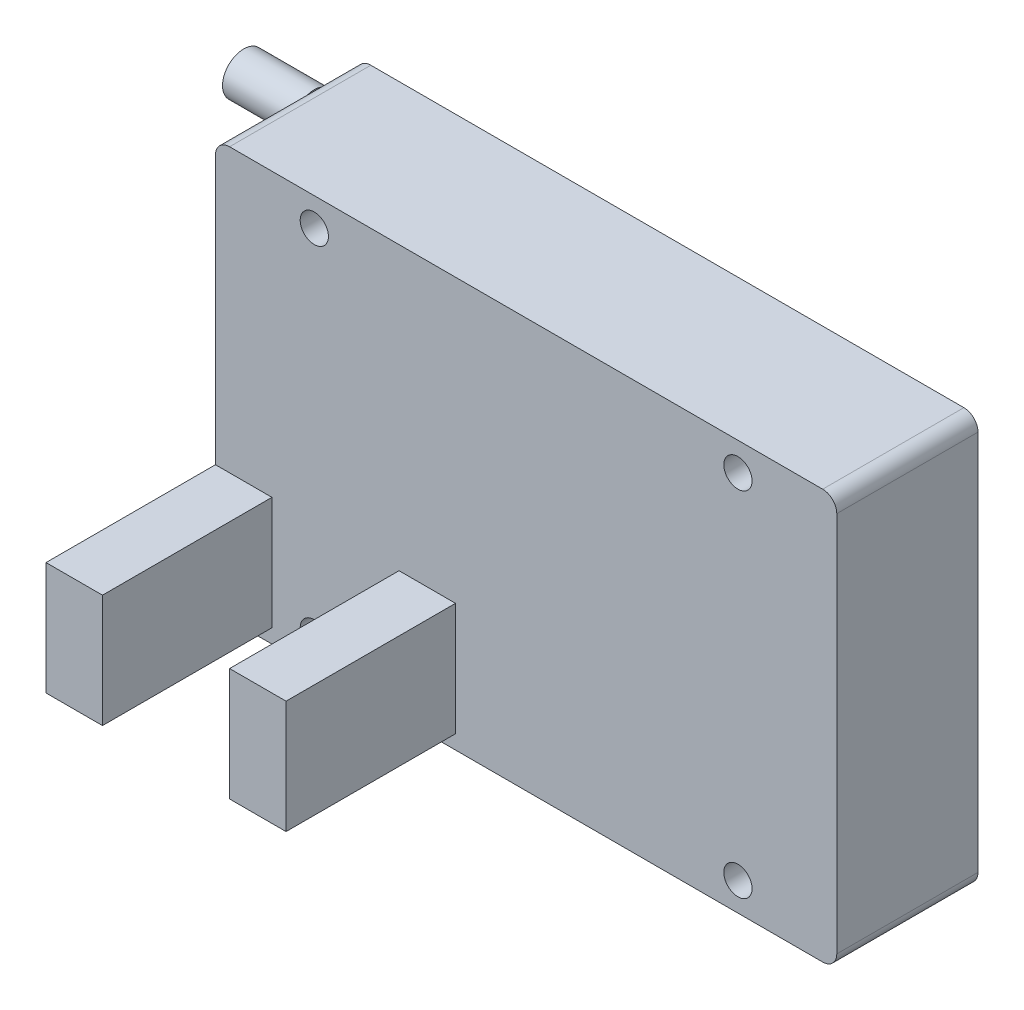
SolidWorks part; units mm, degrees
ref_plane "Front Plane" through (0, 0, 0) normal (1, 0, 0) x (0, 1, 0)
ref_plane "Top Plane" through (0, 0, 0) normal (0, 0, 1) x (0, 1, 0)
ref_plane "Right Plane" through (0, 0, 0) normal (0, 1, 0) x (-1, 0, 0)
sketch "Sketch1" plane through (0, 0, 0) normal (0, 0, 1) x (0, 1, 0)
  line L1 (-13.5, 22) -> (13.5, 22)
  line L2 (-14.5, 21) -> (-14.5, -21)
  line L3 (-13.5, -22) -> (13.5, -22)
  line L4 (14.5, 21) -> (14.5, -21)
  line L5 (-14.5, 22) -> (14.5, -22) construction
  line L6 (-14.5, -22) -> (14.5, 22) construction
  arc A0 (-14.5, -21) -> (-13.5, -22) centre (-13.5, -21) ccw
  arc A1 (13.5, -22) -> (14.5, -21) centre (13.5, -21) ccw
  arc A2 (13.5, 22) -> (14.5, 21) centre (13.5, 21) cw
  arc A3 (-13.5, 22) -> (-14.5, 21) centre (-13.5, 21) ccw
  point P0 (0, 0)
  dimension "D3" = 1
  dimension "D1" = 29
  dimension "D2" = 44
extrude "Boss-Extrude1" add sketch "Sketch1" along normal blind 10
sketch "Sketch2" plane through (-22, 0, 0) normal (-1, 0, 0) x (0, -1, 0)
  line L0 (-13.5, 3) -> (13.5, 3) construction
  line L1 (-13.5, 10) -> (-13.5, 0) construction
  line L2 (13.5, 10) -> (13.5, 0) construction
  line L3 (-14.5, 10) -> (-14.5, 0) construction
  line L4 (14.5, 10) -> (14.5, 0) construction
  line L5 (-13.5, 0) -> (13.5, 0) construction
  circle A0 centre (-12.5, 3) radius 1.5
  circle A1 centre (0.5, 3) radius 1.5
  circle A2 centre (6.5, 3) radius 1.5
  circle A3 centre (11.5, 3) radius 1.5
  dimension "D1" = 3
  dimension "D2" = 2
  dimension "D3" = 3
  dimension "D4" = 5
  dimension "D5" = 6
  dimension "D6" = 3
extrude "Boss-Extrude2" add sketch "Sketch2" along normal blind 5
sketch "Sketch3" plane through (0, 0, 10) normal (0, 0, 1) x (1, 0, 0)
  line L0 (-22, 13.5) -> (-22, -13.5) construction
  line L1 (-22, -5.5) -> (-18, -5.5)
  line L2 (-22, -5.5) -> (-22, -13.5)
  line L3 (-22, -13.5) -> (-18, -13.5)
  line L4 (-5, -5.5) -> (-5, -13.5)
  line L6 (-18, -5.5) -> (-18, -13.5)
  line L7 (-9, -5.5) -> (-9, -13.5)
  line L8 (-9, -5.5) -> (-5, -5.5)
  line L9 (-9, -13.5) -> (-5, -13.5)
  point P11 (-5, -5.5)
  line M10 (-22, 13.5) -> (-22, -13.5)
  dimension "D1" = 8
  dimension "D2" = 17
  dimension "D3" = 4
  dimension "D4" = 4
extrude "Boss-Extrude3" add sketch "Sketch3" along normal blind 12 contours L7 L9 L4 L8 | L6 L1 L3 M10
sketch "Sketch4" plane through (0, 0, 0) normal (0, 0, -1) x (1, 0, 0)
  line L1 (-15, -12.5) -> (15, -12.5) construction
  line L2 (-15, -12.5) -> (-15, 12.5) construction
  line L3 (-15, 12.5) -> (15, 12.5) construction
  line L4 (15, -12.5) -> (15, 12.5) construction
  line L5 (-15, -12.5) -> (15, 12.5) construction
  line L6 (-15, 12.5) -> (15, -12.5) construction
  circle A0 centre (-15, 12.5) radius 1
  circle A1 centre (15, 12.5) radius 1
  circle A2 centre (15, -12.5) radius 1
  circle A3 centre (-15, -12.5) radius 1
  point P0 (0, 0)
  dimension "D1" = 2
  dimension "D2" = 30
  dimension "D3" = 25
extrude "Cut-Extrude1" cut sketch "Sketch4" against normal through all
